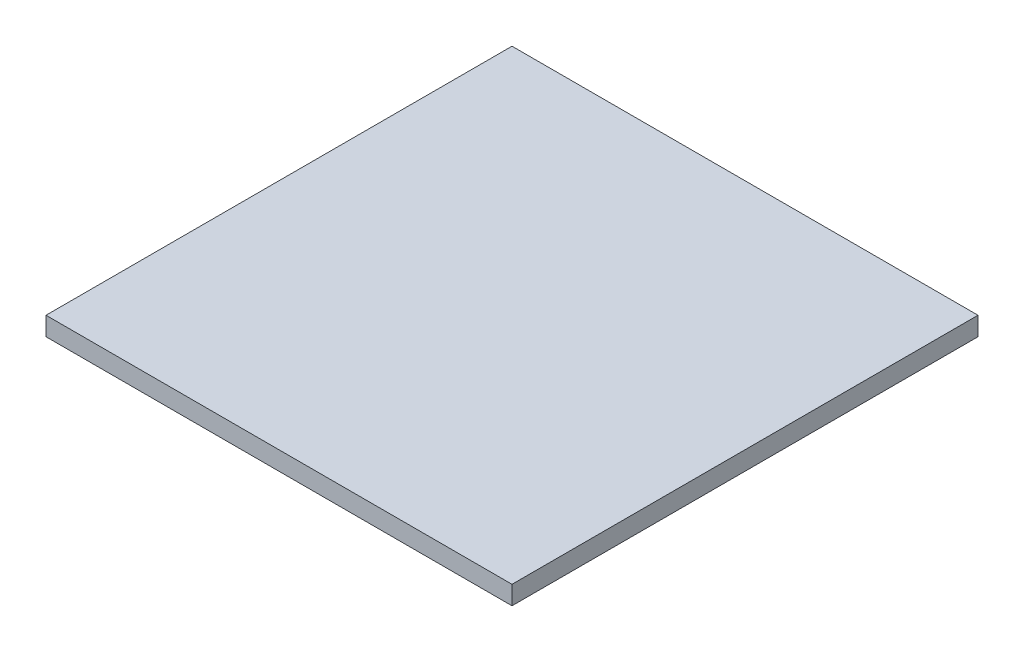
SolidWorks part; units mm, degrees
material "Glass"
ref_plane "Front Plane" through (0, 0, 0) normal (0, 0, 1) x (1, 0, 0)
ref_plane "Top Plane" through (0, 0, 0) normal (0, 1, 0) x (1, 0, 0)
ref_plane "Right Plane" through (0, 0, 0) normal (1, 0, 0) x (0, 0, -1)
sketch "Sketch1" plane through (0, 0, 0) normal (0, 1, 0) x (1, 0, 0)
  line L0 (0, 0) -> (0, 250)
  line L1 (0, 0) -> (250, 0)
  line L2 (0, 250) -> (250, 250)
  line L3 (250, 0) -> (250, 250)
  dimension "D1" = 250
  dimension "D2" = 250
extrude "Boss-Extrude1" add sketch "Sketch1" along normal blind 10
